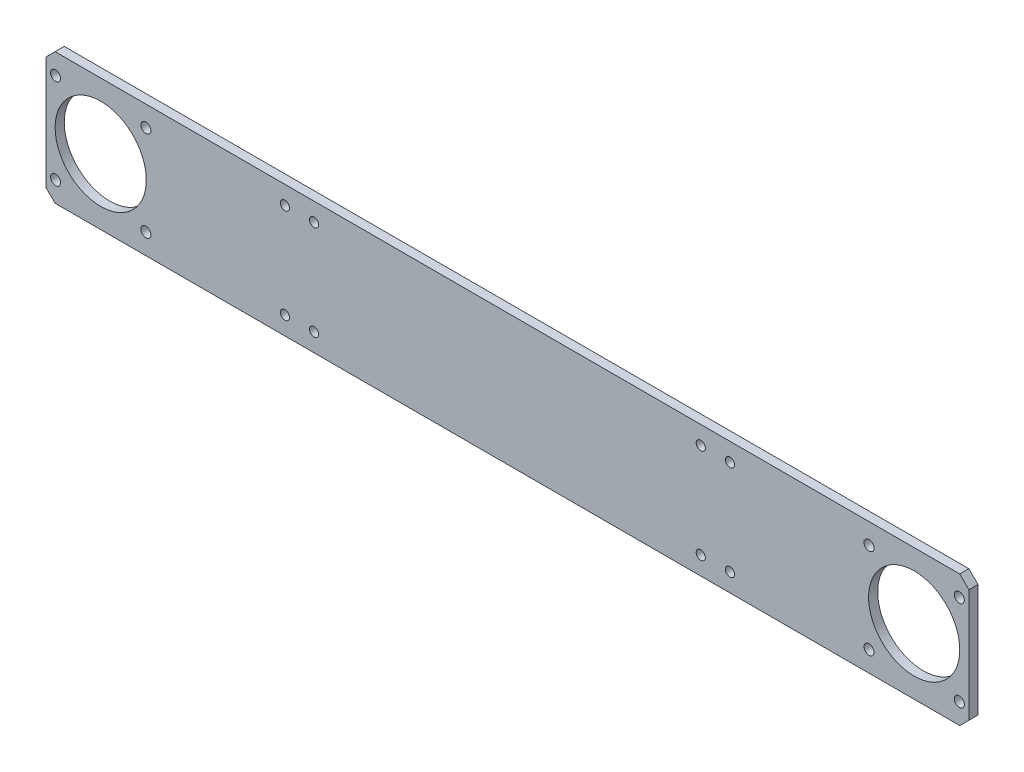
SolidWorks part; units mm, degrees
material "合金钢"
ref_plane "前视基准面" through (0, 0, 0) normal (0, 0, 1) x (1, 0, 0)
ref_plane "上视基准面" through (0, 0, 0) normal (0, 1, 0) x (1, 0, 0)
ref_plane "右视基准面" through (0, 0, 0) normal (1, 0, 0) x (0, 0, -1)
sketch "草图1" plane through (0, 0, 0) normal (0, 0, 1) x (1, 0, 0)
  line L1 (253, 36) -> (-253, 36)
  line L2 (253, 36) -> (253, -36)
  line L3 (253, -36) -> (-253, -36)
  line L4 (-253, 36) -> (-253, -36)
  line L5 (0, -36) -> (0, 36) construction
  line L6 (253, 0) -> (-253, 0) construction
  line L7 (247.7487, 24.7487) -> (198.2513, 24.7487) construction
  line L8 (247.7487, 24.7487) -> (247.7487, -24.7487) construction
  line L9 (247.7487, -24.7487) -> (198.2513, -24.7487) construction
  line L10 (198.2513, 24.7487) -> (198.2513, -24.7487) construction
  line L11 (223, -24.7487) -> (223, 24.7487) construction
  line L12 (247.7487, 0) -> (198.2513, 0) construction
  circle A0 centre (223, 0) radius 25
  circle A1 centre (247.7487, 24.7487) radius 2.75
  circle A2 centre (198.2513, 24.7487) radius 2.75
  circle A3 centre (198.2513, -24.7487) radius 2.75
  circle A4 centre (247.7487, -24.7487) radius 2.75
  circle A5 centre (-247.7487, -24.7487) radius 2.75
  circle A6 centre (-247.7487, 24.7487) radius 2.75
  circle A7 centre (-198.2513, 24.7487) radius 2.75
  circle A8 centre (-198.2513, -24.7487) radius 2.75
  circle A9 centre (-223, 0) radius 25
  circle A12 centre (223, 0) radius 35 construction
  point P0 (0, 0)
  dimension "D2" = 50
  dimension "D5" = 30
  dimension "D6" = 5.5
  dimension "D7" = 5.5
  dimension "D8" = 5.5
  dimension "D9" = 446
  dimension "5.5" = 5.5
  dimension "D3" = 70
  dimension "D1" = 72
extrude "凸台-拉伸1" add sketch "草图1" along normal blind 5
chamfer "倒角1" distance 5 angle 45 4 edges at (-253, -36, 2.5) (-253, 36, 2.5) (253, -36, 2.5) (253, 36, 2.5)
sketch "草图2" plane through (0, 0, 5) normal (0, 0, 1) x (1, 0, 0)
  line L1 (248, 36) -> (-248, 36) construction
  line L2 (-248, -36) -> (248, -36) construction
  line L3 (0, 36) -> (0, -36) construction
  line L4 (-122, 26) -> (-106, -26) construction
  line L5 (122, 26) -> (106, -26) construction
  circle A0 centre (-122, 26) radius 2.5
  circle A1 centre (-122, -26) radius 2.5
  circle A2 centre (-106, 26) radius 2.5
  circle A3 centre (-106, -26) radius 2.5
  circle A4 centre (106, -26) radius 2.5
  circle A5 centre (106, 26) radius 2.5
  circle A6 centre (122, -26) radius 2.5
  circle A7 centre (122, 26) radius 2.5
  point P8 (-114, 0)
  point P9 (114, 0)
  dimension "D5" = 5
  dimension "D1" = 228
  dimension "D3" = 52
  dimension "D4" = 16
extrude "切除-拉伸1" cut sketch "草图2" against normal through all
